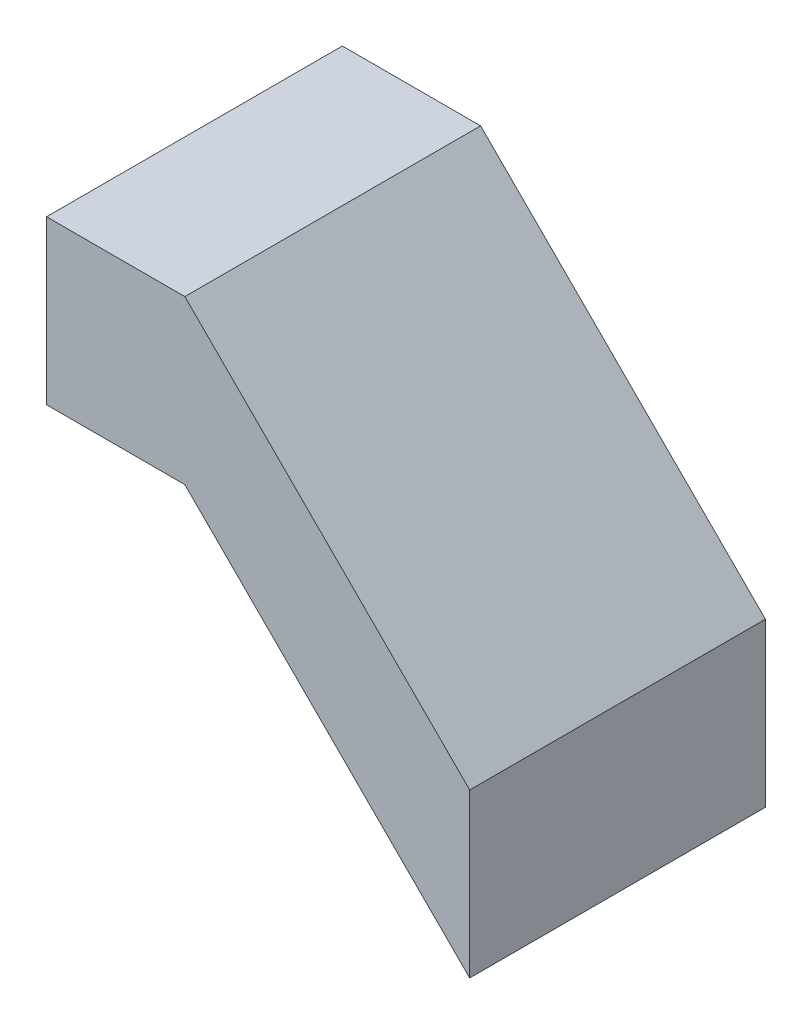
SolidWorks part; units mm, degrees
ref_plane "Alzado" through (0, 0, 0) normal (0, 0, 1) x (1, 0, 0)
ref_plane "Planta" through (0, 0, 0) normal (0, 1, 0) x (1, 0, 0)
ref_plane "Vista lateral" through (0, 0, 0) normal (1, 0, 0) x (0, 0, -1)
sketch "Croquis1" plane through (0, 0, 0) normal (0, 0, 1) x (1, 0, 0)
  line L0 (193.7545, -55.9999) -> (193.7545, -50.9999)
  line L1 (206.7451, -64.7452) -> (206.7451, -59.7452)
  line L2 (197.9998, -55.9999) -> (197.9998, -50.9999) construction
  line L3 (193.7545, -50.9999) -> (197.9998, -50.9999)
  line L4 (197.9998, -50.9999) -> (206.7451, -59.7452)
  line L5 (193.7545, -55.9999) -> (197.9998, -55.9999)
  line L6 (200.7451, -58.7452) -> (200.7451, -56.2452)
  line L7 (200.7451, -58.7452) -> (197.9998, -55.9999)
  line L8 (204.7451, -62.7452) -> (204.7451, -60.2452)
  line L9 (200.7451, -56.2452) -> (204.7451, -60.2452)
  line L11 (204.7451, -62.7452) -> (206.7451, -64.7452)
  dimension "D1" = 50.9999
  dimension "D2" = 56.2452
extrude "Saliente-Extruir1" add sketch "Croquis1" against normal up to vertex (9.08 mm away)
sketch "Croquis2" plane through (0, 0, 0) normal (0, 0, 1) x (1, 0, 0)
  line L0 (200.7451, -58.7452) -> (200.7451, -56.2452)
  line L1 (200.7451, -56.2452) -> (204.7451, -60.2452)
  line L2 (204.7451, -60.2452) -> (204.7451, -62.7452)
  line L3 (204.7451, -62.7452) -> (200.7451, -58.7452)
extrude "Saliente-Extruir2" add sketch "Croquis2" against normal up to vertex (1.5 mm away)
sketch "Croquis3" plane through (0, 0, -9.08) normal (0, 0, -1) x (-1, 0, 0)
  line L0 (-204.7451, -62.7452) -> (-204.7451, -60.2452)
  line L1 (-204.7451, -60.2452) -> (-200.7451, -56.2452)
  line L2 (-200.7451, -56.2452) -> (-200.7451, -58.7452)
  line L3 (-200.7451, -58.7452) -> (-204.7451, -62.7452)
extrude "Saliente-Extruir3" add sketch "Croquis3" against normal up to vertex (4.08 mm away)
